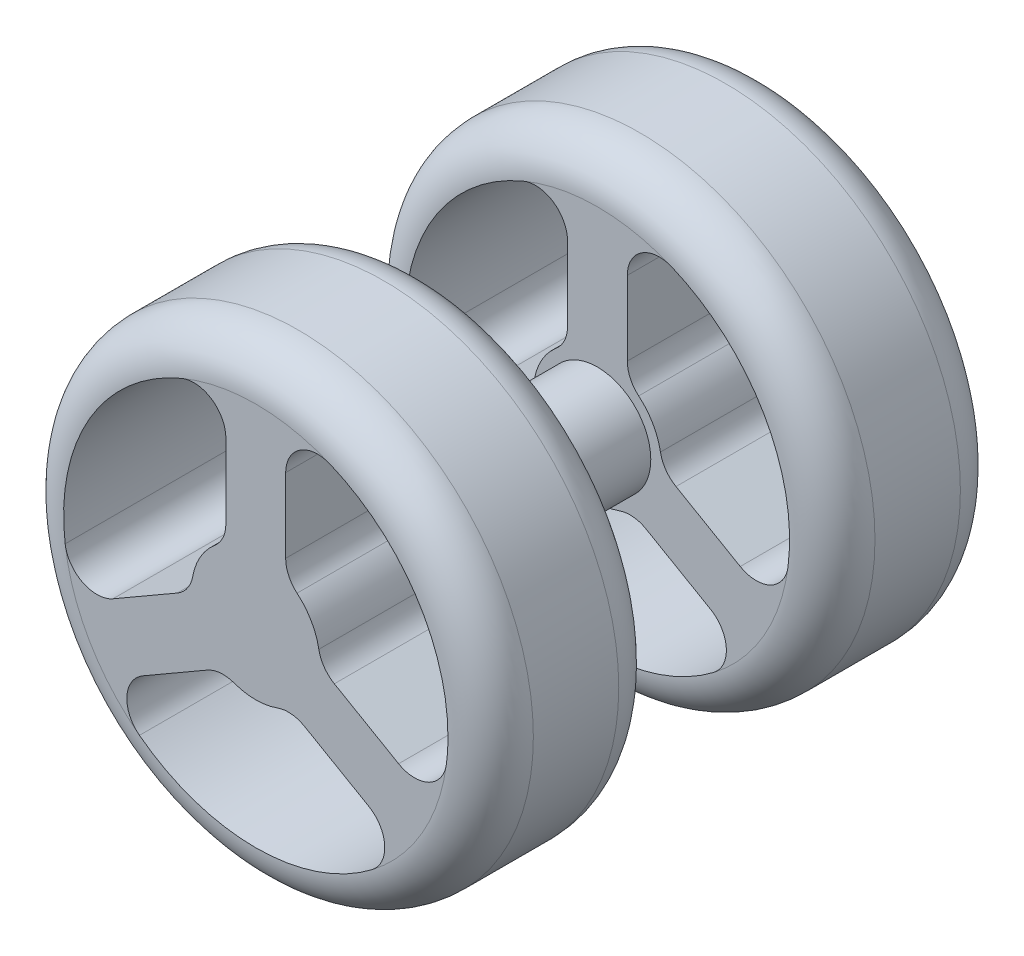
SolidWorks part; units mm, degrees
ref_plane "Front Plane" through (0, 0, 0) normal (0, 0, 1) x (1, 0, 0)
ref_plane "Top Plane" through (0, 0, 0) normal (0, 1, 0) x (1, 0, 0)
ref_plane "Right Plane" through (0, 0, 0) normal (1, 0, 0) x (0, 0, -1)
sketch "Sketch1" plane through (0, 0, 0) normal (0, 0, 1) x (1, 0, 0)
  circle A0 centre (0, 0) radius 27.94
  dimension "D1" = 55.88
extrude "Boss-Extrude1" add sketch "Sketch1" along normal blind 20.32
sketch "Sketch2" plane through (0, 0, 0) normal (0, 0, -1) x (-1, 0, 0)
  circle A0 centre (0, 0) radius 6.35
  dimension "D2" = 12.7
extrude "Boss-Extrude2" add sketch "Sketch2" along normal blind 20.32
sketch "Sketch3" plane through (0, 0, -20.32) normal (0, 0, -1) x (-1, 0, 0)
  circle A0 centre (0, 0) radius 27.94
  dimension "D2" = 55.88
extrude "Boss-Extrude3" add sketch "Sketch3" along normal blind 20.32
fillet "Fillet1" radius 5.08 1 edges at (27.94, 0, 20.32)
fillet "Fillet2" radius 5.08 1 edges at (27.94, 0, 0)
fillet "Fillet3" radius 5.08 1 edges at (-27.94, 0, -20.32)
fillet "Fillet4" radius 5.08 1 edges at (-27.94, 0, -40.64)
sketch "Sketch4" plane through (0, 0, -40.64) normal (0, 0, -1) x (-1, 0, 0)
  line L0 (0, 7.62) -> (0, 22.86) construction
  line L1 (-3.556, 8.74) -> (-3.556, 17.5683)
  line L2 (3.556, 8.74) -> (3.556, 17.5683)
  line L3 (9.347, -1.2904) -> (16.9926, -5.7046)
  line L4 (5.791, -7.4496) -> (13.4366, -11.8637)
  line L5 (-5.791, -7.4496) -> (-13.4366, -11.8637)
  line L6 (-9.347, -1.2904) -> (-16.9926, -5.7046)
  arc A0 (-13.8379, -18.1959) -> (13.8379, -18.1959) centre (0, 0) ccw
  arc A1 (7.5014, 1.3394) -> (4.9107, 5.8266) centre (0, 0) ccw
  arc A2 (-4.9107, 5.8266) -> (-7.5014, 1.3394) centre (0, 0) ccw
  arc A3 (-2.5907, -7.1661) -> (2.5907, -7.1661) centre (0, 0) ccw
  arc A4 (-3.556, 17.5683) -> (-8.8392, 21.0819) centre (-7.366, 17.5683) ccw
  arc A5 (8.8392, 21.0819) -> (3.556, 17.5683) centre (7.366, 17.5683) ccw
  arc A6 (-4.9107, 5.8266) -> (-3.556, 8.74) centre (-7.366, 8.74) ccw
  arc A7 (3.556, 8.74) -> (4.9107, 5.8266) centre (7.366, 8.74) ccw
  arc A8 (16.9926, -5.7046) -> (22.6771, -2.886) centre (18.8976, -2.405) ccw
  arc A9 (7.5014, 1.3394) -> (9.347, -1.2904) centre (11.252, 2.0092) ccw
  arc A10 (5.791, -7.4496) -> (2.5907, -7.1661) centre (3.886, -10.7491) ccw
  arc A11 (13.8379, -18.1959) -> (13.4366, -11.8637) centre (11.5316, -15.1633) ccw
  arc A12 (-13.4366, -11.8637) -> (-13.8379, -18.1959) centre (-11.5316, -15.1633) ccw
  arc A13 (-2.5907, -7.1661) -> (-5.791, -7.4496) centre (-3.886, -10.7491) ccw
  arc A14 (-9.347, -1.2904) -> (-7.5014, 1.3394) centre (-11.252, 2.0092) ccw
  arc A15 (-22.6771, -2.886) -> (-16.9926, -5.7046) centre (-18.8976, -2.405) ccw
  arc A16 (22.6771, -2.886) -> (8.8392, 21.0819) centre (0, 0) ccw
  arc A17 (-8.8392, 21.0819) -> (-22.6771, -2.886) centre (0, 0) ccw
  point P46 (0, 0)
  dimension "D2" = 45.72
  dimension "D3" = 15.24
  dimension "D6" = 7.62
  dimension "D7" = 7.62
  dimension "D8" = 7.62
  dimension "D9" = 7.62
  dimension "D4" = 3.556
  dimension "D5" = 3.556
  dimension "D10" = 3
sketch "Sketch5" plane through (0, 0, 0) normal (0, 1, 0) x (1, 0, 0)
  line L0 (0, 32.8922) -> (0, -10.16) construction
extrude "Cut-Extrude1" cut sketch "Sketch4" against normal through all
